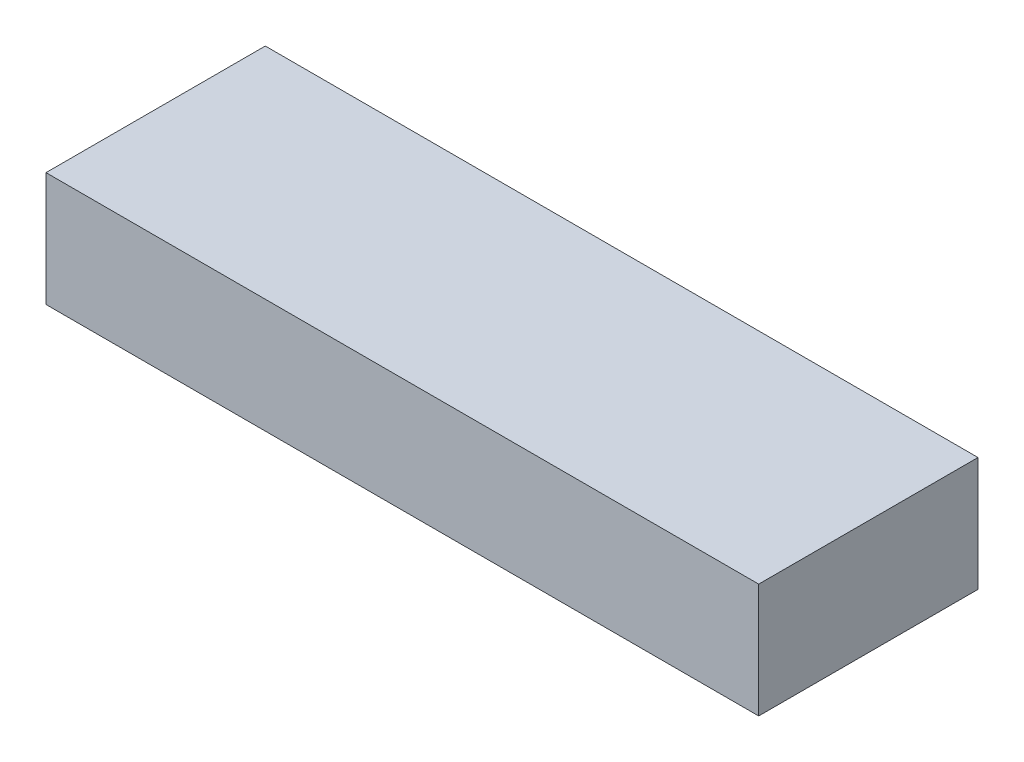
SolidWorks part; units mm, degrees
ref_plane "Plan de face" through (0, 0, 0) normal (0, 0, 1) x (1, 0, 0)
ref_plane "Plan de dessus" through (0, 0, 0) normal (0, 1, 0) x (1, 0, 0)
ref_plane "Plan de droite" through (0, 0, 0) normal (1, 0, 0) x (0, 0, -1)
sketch "Esquisse1" plane through (0, 0, 0) normal (0, 1, 0) x (1, 0, 0)
  line L1 (-78, 24) -> (78, 24)
  line L2 (-78, 24) -> (-78, -24)
  line L3 (-78, -24) -> (78, -24)
  line L4 (78, 24) -> (78, -24)
  line L5 (-78, 24) -> (78, -24) construction
  line L6 (-78, -24) -> (78, 24) construction
  point P0 (0, 0)
  dimension "D1" = 156
  dimension "D2" = 48
extrude "Boss.-Extru.1" add sketch "Esquisse1" along normal blind 25
